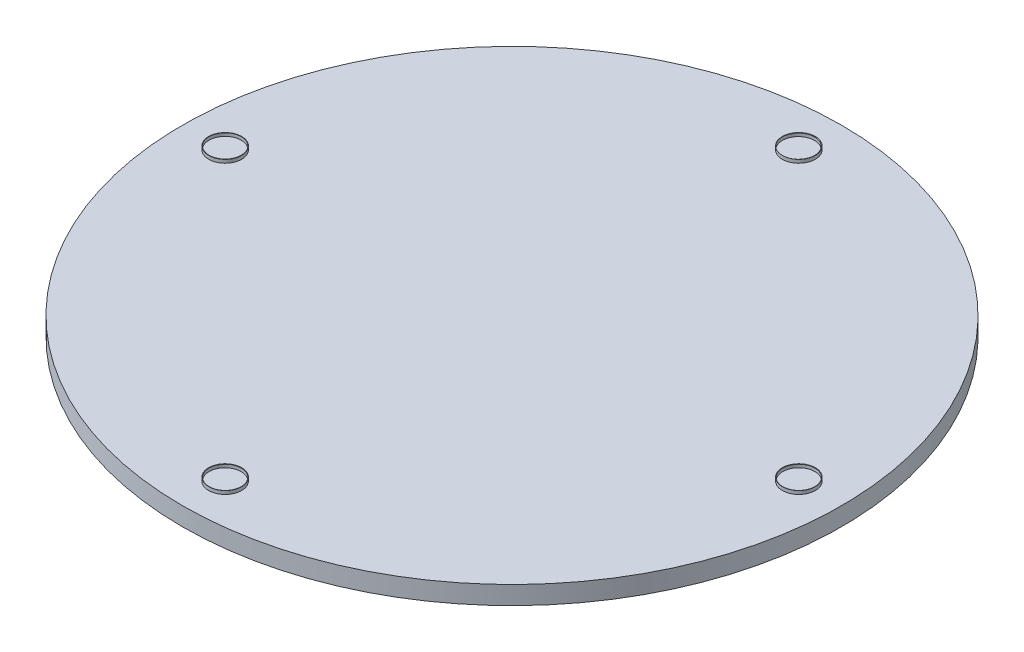
SolidWorks part; units mm, degrees
ref_plane "Front Plane" through (0, 0, 0) normal (0, 0, 1) x (1, 0, 0)
ref_plane "Top Plane" through (0, 0, 0) normal (0, 1, 0) x (1, 0, 0)
ref_plane "Right Plane" through (0, 0, 0) normal (1, 0, 0) x (0, 0, -1)
sketch "Sketch1" plane through (0, 0, 0) normal (0, 1, 0) x (1, 0, 0)
  circle A0 centre (0, 0) radius 540
extrude "Boss-Extrude1" add sketch "Sketch1" along normal blind 30 contours A0
sketch "Sketch2" plane through (0, 30, 0) normal (0, 1, 0) x (1, 0, 0)
  line L0 (540, 0) -> (-540, 0)
  line L1 (0, -540) -> (0, 540)
  circle A0 centre (0, 0) radius 540 construction
  point P6 (0, 0)
  point P10 (0, 0)
sketch "Sketch3" plane through (0, 30, 0) normal (0, 1, 0) x (1, 0, 0)
  line L0 (0, 540) -> (0, 470)
  line L1 (-540, 0) -> (-470, 0)
  line L2 (540, 0) -> (470, 0)
sketch "Sketch4" plane through (0, 0, 0) normal (1, 0, 0) x (0, 0, -1)
  line L0 (-540, 30) -> (-470, 30)
  line L1 (-540, 30) -> (540, 30) construction
sketch "Sketch5" plane through (0, 0, 0) normal (1, 0, 0) x (0, 0, -1)
  line L0 (-540, 30) -> (-470, 30)
sketch "Sketch7" plane through (0, 30, 0) normal (0, 1, 0) x (1, 0, 0)
  circle A0 centre (-470, 0) radius 27
extrude "Boss-Extrude2" add sketch "Sketch7" along normal blind 5.5 contours A0
sketch "Sketch10" plane through (0, 35.5, 0) normal (0, 1, 0) x (1, 0, 0)
  circle A0 centre (-470, 0) radius 26.3
extrude "Cut-Extrude1" cut sketch "Sketch10" against normal blind 5
mirror "Mirror1" about plane through (0, 0, 0) normal (1, 0, 0) of "Boss-Extrude2"
sketch "Sketch11" plane through (0, 30, 0) normal (0, 1, 0) x (1, 0, 0)
  circle A0 centre (0, 470) radius 27
extrude "Boss-Extrude3" add sketch "Sketch11" along normal blind 5.5 contours A0
sketch "Sketch12" plane through (0, 35.5, 0) normal (0, 1, 0) x (1, 0, 0)
  circle A0 centre (0, 469.3542) radius 26.3
extrude "Cut-Extrude2" cut sketch "Sketch12" against normal blind 5
mirror "Mirror2" about plane through (0, 0, 0) normal (0, 0, 1) of "Boss-Extrude3"
sketch "Sketch13" plane through (0, 35.5, 0) normal (0, 1, 0) x (1, 0, 0)
  circle A0 centre (0.2313, -470.275) radius 26.3
extrude "Cut-Extrude3" cut sketch "Sketch13" against normal blind 5
sketch "Sketch14" plane through (0, 35.5, 0) normal (0, 1, 0) x (1, 0, 0)
  circle A0 centre (470.2311, -0.2736) radius 26.3
extrude "Cut-Extrude4" cut sketch "Sketch14" against normal blind 5
